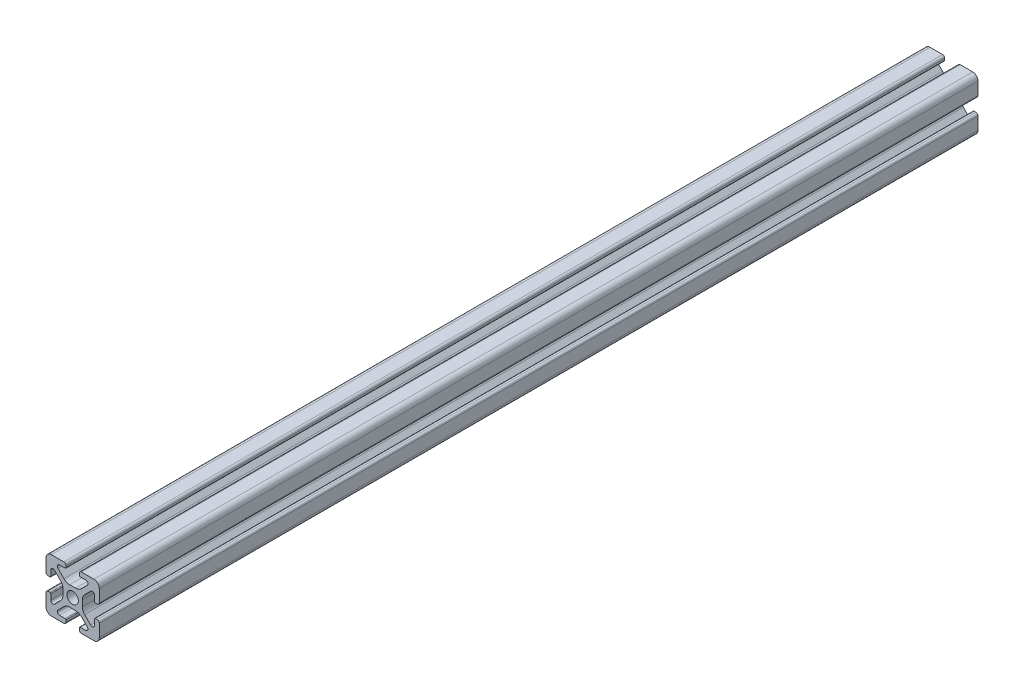
SolidWorks part; units mm, degrees
material "3.0205 (EN-AW 1200)"
ref_plane "Plan de face" through (0, 0, 0) normal (0, 0, 1) x (1, 0, 0)
ref_plane "Plan de dessus" through (0, 0, 0) normal (0, 1, 0) x (1, 0, 0)
ref_plane "Plan de droite" through (0, 0, 0) normal (1, 0, 0) x (0, 0, -1)
ref_plane "Plan1" through (0, 0, 0) normal (0, 0, -1) x (-1, 0, 0)
sketch "Esquisse1" plane through (0, 0, 0) normal (0, 0, -1) x (-1, 0, 0)
  line L0 (-12.5, 0.8) -> (-12.5, 1.5)
  line L1 (-12.8, 1.8) -> (-14.9176, 1.8)
  line L2 (-15.5062, 3.221) -> (-13.2559, 5.4713)
  line L3 (-11.1346, 6.35) -> (-8.8654, 6.35)
  line L4 (-6.7441, 5.4713) -> (-4.4938, 3.221)
  line L5 (-5.0824, 1.8) -> (-7.2, 1.8)
  line L6 (-7.5, 1.5) -> (-7.5, 0.8)
  line L7 (-6.7, 0) -> (-2, 0)
  line L8 (0, 2) -> (0, 6.7)
  line L9 (-0.8, 7.5) -> (-1.5, 7.5)
  line L10 (-1.8, 7.2) -> (-1.8, 5.0824)
  line L11 (-3.221, 4.4938) -> (-5.4713, 6.7441)
  line L12 (-6.35, 8.8654) -> (-6.35, 11.1346)
  line L13 (-5.4713, 13.2559) -> (-3.221, 15.5062)
  line L14 (-1.8, 14.9176) -> (-1.8, 12.8)
  line L15 (-1.5, 12.5) -> (-0.8, 12.5)
  line L16 (0, 13.3) -> (0, 18)
  line L17 (-2, 20) -> (-6.7, 20)
  line L18 (-7.5, 19.2) -> (-7.5, 18.5)
  line L19 (-7.2, 18.2) -> (-5.0824, 18.2)
  line L20 (-4.4938, 16.779) -> (-6.7441, 14.5287)
  line L21 (-8.8654, 13.65) -> (-11.1346, 13.65)
  line L22 (-13.2559, 14.5287) -> (-15.5062, 16.779)
  line L23 (-14.9176, 18.2) -> (-12.8, 18.2)
  line L24 (-12.5, 18.5) -> (-12.5, 19.2)
  line L25 (-13.3, 20) -> (-18, 20)
  line L26 (-20, 18) -> (-20, 13.3)
  line L27 (-19.2, 12.5) -> (-18.5, 12.5)
  line L28 (-18.2, 12.8) -> (-18.2, 14.9176)
  line L29 (-16.779, 15.5062) -> (-14.5287, 13.2559)
  line L30 (-13.65, 11.1346) -> (-13.65, 8.8654)
  line L31 (-14.5287, 6.7441) -> (-16.779, 4.4938)
  line L32 (-18.2, 5.0824) -> (-18.2, 7.2)
  line L33 (-18.5, 7.5) -> (-19.2, 7.5)
  line L34 (-20, 6.7) -> (-20, 2)
  line L35 (-18, 0) -> (-13.3, 0)
  arc A0 (-12.5, 1.5) -> (-12.8, 1.8) centre (-12.8, 1.5) ccw
  arc A1 (-14.9176, 1.8) -> (-15.5062, 3.221) centre (-14.9176, 2.6324) cw
  arc A2 (-13.2559, 5.4713) -> (-11.1346, 6.35) centre (-11.1346, 3.35) cw
  arc A3 (-8.8654, 6.35) -> (-6.7441, 5.4713) centre (-8.8654, 3.35) cw
  arc A4 (-4.4938, 3.221) -> (-5.0824, 1.8) centre (-5.0824, 2.6324) cw
  arc A5 (-7.2, 1.8) -> (-7.5, 1.5) centre (-7.2, 1.5) ccw
  arc A6 (-7.5, 0.8) -> (-6.7, 0) centre (-6.7, 0.8) ccw
  arc A7 (-2, 0) -> (0, 2) centre (-2, 2) ccw
  arc A8 (0, 6.7) -> (-0.8, 7.5) centre (-0.8, 6.7) ccw
  arc A9 (-1.5, 7.5) -> (-1.8, 7.2) centre (-1.5, 7.2) ccw
  arc A10 (-1.8, 5.0824) -> (-3.221, 4.4938) centre (-2.6324, 5.0824) cw
  arc A11 (-5.4713, 6.7441) -> (-6.35, 8.8654) centre (-3.35, 8.8654) cw
  arc A12 (-6.35, 11.1346) -> (-5.4713, 13.2559) centre (-3.35, 11.1346) cw
  arc A13 (-3.221, 15.5062) -> (-1.8, 14.9176) centre (-2.6324, 14.9176) cw
  arc A14 (-1.8, 12.8) -> (-1.5, 12.5) centre (-1.5, 12.8) ccw
  arc A15 (-0.8, 12.5) -> (0, 13.3) centre (-0.8, 13.3) ccw
  arc A16 (0, 18) -> (-2, 20) centre (-2, 18) ccw
  arc A17 (-6.7, 20) -> (-7.5, 19.2) centre (-6.7, 19.2) ccw
  arc A18 (-7.5, 18.5) -> (-7.2, 18.2) centre (-7.2, 18.5) ccw
  arc A19 (-5.0824, 18.2) -> (-4.4938, 16.779) centre (-5.0824, 17.3676) cw
  arc A20 (-6.7441, 14.5287) -> (-8.8654, 13.65) centre (-8.8654, 16.65) cw
  arc A21 (-11.1346, 13.65) -> (-13.2559, 14.5287) centre (-11.1346, 16.65) cw
  arc A22 (-15.5062, 16.779) -> (-14.9176, 18.2) centre (-14.9176, 17.3676) cw
  arc A23 (-12.8, 18.2) -> (-12.5, 18.5) centre (-12.8, 18.5) ccw
  arc A24 (-12.5, 19.2) -> (-13.3, 20) centre (-13.3, 19.2) ccw
  arc A25 (-18, 20) -> (-20, 18) centre (-18, 18) ccw
  arc A26 (-20, 13.3) -> (-19.2, 12.5) centre (-19.2, 13.3) ccw
  arc A27 (-18.5, 12.5) -> (-18.2, 12.8) centre (-18.5, 12.8) ccw
  arc A28 (-18.2, 14.9176) -> (-16.779, 15.5062) centre (-17.3676, 14.9176) cw
  arc A29 (-14.5287, 13.2559) -> (-13.65, 11.1346) centre (-16.65, 11.1346) cw
  arc A30 (-13.65, 8.8654) -> (-14.5287, 6.7441) centre (-16.65, 8.8654) cw
  arc A31 (-16.779, 4.4938) -> (-18.2, 5.0824) centre (-17.3676, 5.0824) cw
  arc A32 (-18.2, 7.2) -> (-18.5, 7.5) centre (-18.5, 7.2) ccw
  arc A33 (-19.2, 7.5) -> (-20, 6.7) centre (-19.2, 6.7) ccw
  arc A34 (-20, 2) -> (-18, 0) centre (-18, 2) ccw
  arc A35 (-13.3, 0) -> (-12.5, 0.8) centre (-13.3, 0.8) ccw
  circle A36 centre (-10, 10) radius 2.15
extrude "Boss.-Extru.1" add sketch "Esquisse1" against normal blind 330
